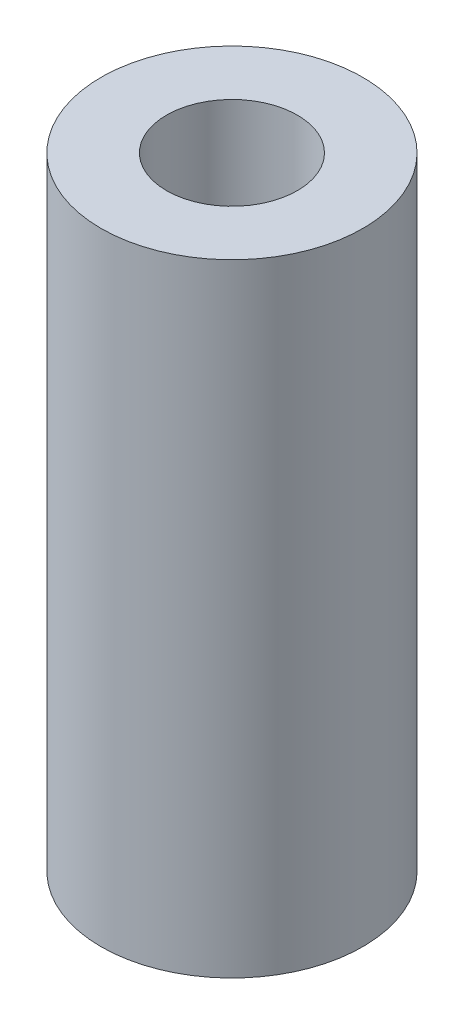
SolidWorks part; units mm, degrees
material "6061-T6 (SS)"
ref_plane "Front Plane" through (0, 0, 0) normal (0, 0, 1) x (1, 0, 0)
ref_plane "Top Plane" through (0, 0, 0) normal (0, 1, 0) x (1, 0, 0)
ref_plane "Right Plane" through (0, 0, 0) normal (1, 0, 0) x (0, 0, -1)
sketch "Sketch1" plane through (0, 0, 0) normal (0, 1, 0) x (1, 0, 0)
  circle A0 centre (0, 0) radius 6.35
  circle A1 centre (0, 0) radius 3.175
  dimension "D1" = 12.7
  dimension "D2" = 6.35
extrude "Boss-Extrude1" add sketch "Sketch1" along normal blind 30.1752
